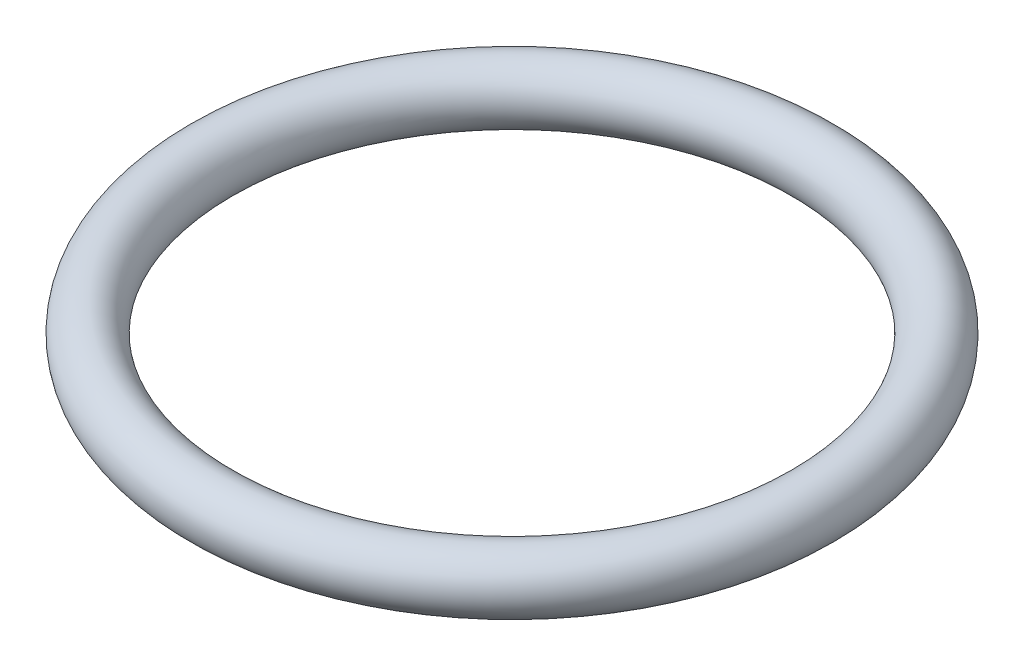
SolidWorks part; units mm, degrees
material "Эпихлоргидрин"
ref_plane "Спереди" through (0, 0, 0) normal (0, 0, 1) x (1, 0, 0)
ref_plane "Сверху" through (0, 0, 0) normal (0, 1, 0) x (1, 0, 0)
ref_plane "Справа" through (0, 0, 0) normal (1, 0, 0) x (0, 0, -1)
sketch "Эскиз1" plane through (0, 0, 0) normal (0, 0, 1) x (1, 0, 0)
  line L1 (0, -1000) -> (0, 49000) construction
  circle A0 centre (-25.5, 0) radius 2.5
  point P2 (-25.5, 9.5762)
  dimension "D1" = 5
  dimension "D2" = 51
revolve "Повернуть1" add sketch "Эскиз1" angle 360 about L1
